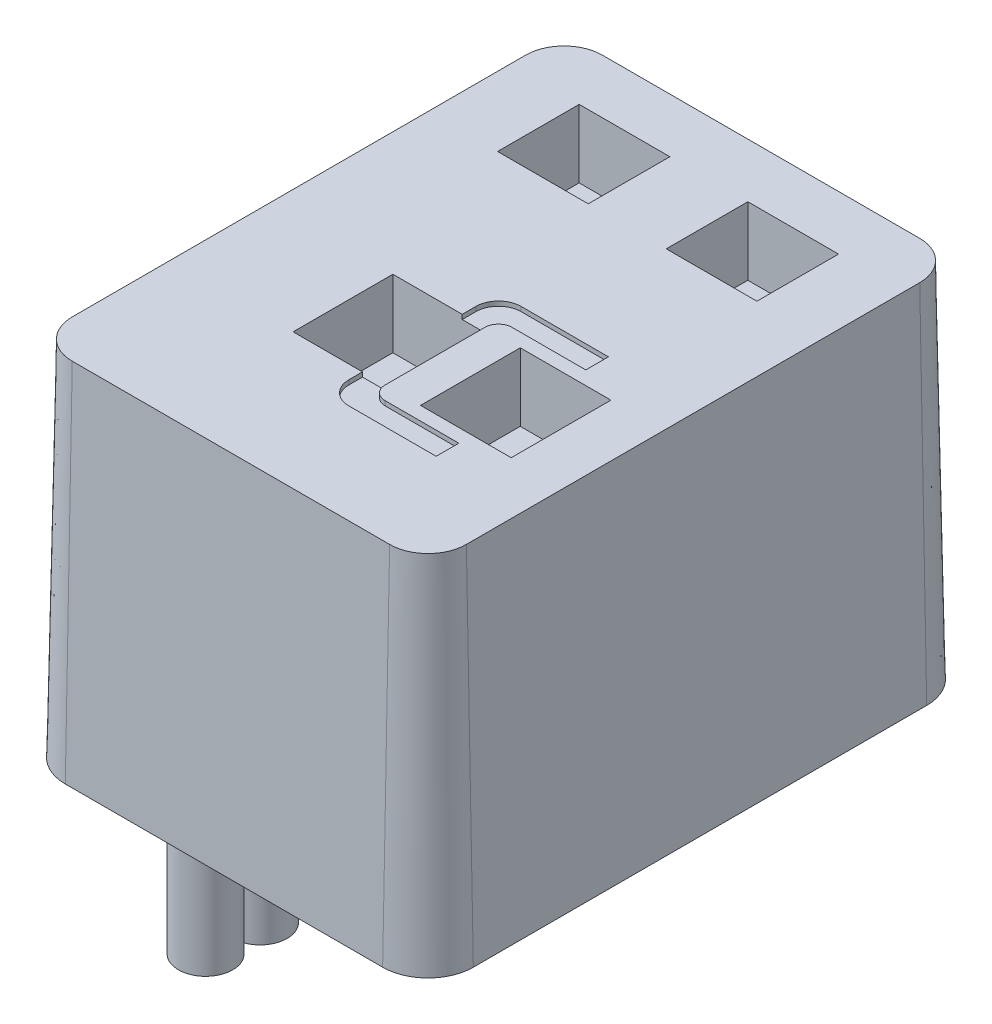
SolidWorks part; units mm, degrees
ref_plane "Alzado" through (0, 0, 0) normal (0, 0, 1) x (1, 0, 0)
ref_plane "Planta" through (0, 0, 0) normal (0, 1, 0) x (1, 0, 0)
ref_plane "Vista lateral" through (0, 0, 0) normal (1, 0, 0) x (0, 0, -1)
ref_plane "Plano1"
sketch "Croquis1" plane through (0, 0, 0) normal (0, 1, 0) x (-1, 0, 0)
  line L0 (4.5, -5) -> (4.5, 5)
  line L1 (3.5, 6) -> (-3.5, 6)
  line L2 (-4.5, 5) -> (-4.5, -5)
  line L3 (-3.5, -6) -> (3.5, -6)
  arc A0 (3.5, -6) -> (4.5, -5) centre (3.5, -5) ccw
  arc A1 (4.5, 5) -> (3.5, 6) centre (3.5, 5) ccw
  arc A2 (-3.5, 6) -> (-4.5, 5) centre (-3.5, 5) ccw
  arc A3 (-4.5, -5) -> (-3.5, -6) centre (-3.5, -5) ccw
  dimension "D1" = 1
  dimension "D2" = 1
extrude "Extrusión1" add sketch "Croquis1" along normal blind 8 draft 1.099
sketch "Croquis2" plane through (0, 8, 0) normal (0, 1, 0) x (-1, 0, 0)
  line L0 (-0.375, 2.85) -> (-0.375, 0.65)
  line L1 (-0.375, 0.65) -> (1.625, 0.65)
  line L2 (1.625, 0.65) -> (1.625, 2.85)
  line L3 (1.625, 2.85) -> (-0.375, 2.85)
  line L4 (-3.185, 2.85) -> (-3.185, 0.65)
  line L5 (-3.185, 0.65) -> (-1.185, 0.65)
  line L6 (-1.185, 0.65) -> (-1.185, 2.85)
  line L7 (-1.185, 2.85) -> (-3.185, 2.85)
  line L8 (-2.905, -2.85) -> (-2.905, -4.65)
  line L9 (-2.905, -4.65) -> (-0.905, -4.65)
  line L10 (-0.905, -4.65) -> (-0.905, -2.85)
  line L11 (-0.905, -2.85) -> (-2.905, -2.85)
  line L12 (0.815, -2.85) -> (0.815, -4.65)
  line L13 (0.815, -4.65) -> (2.815, -4.65)
  line L14 (2.815, -4.65) -> (2.815, -2.85)
  line L15 (2.815, -2.85) -> (0.815, -2.85)
  line L16 (3.5, 5.8465) -> (-3.5, 5.8465) construction
  line L17 (-3.5, -5.8465) -> (3.5, -5.8465) construction
  dimension "D1" = 2
  dimension "D2" = 1.8
  dimension "D3" = 2
  dimension "D4" = 1.8
  dimension "D5" = 10.4965
  dimension "D6" = 2
  dimension "D7" = 2.2
  dimension "D8" = 2
  dimension "D9" = 2.2
  dimension "D10" = 8.6965
extrude "Extrusión2" cut sketch "Croquis2" against normal blind 1.5
sketch "Croquis3" plane through (0, 8, 0) normal (0, 1, 0) x (-1, 0, 0)
  line L0 (0.095, 0.35) -> (0.095, 3.15)
  line L1 (-0.405, 3.65) -> (-2.33, 3.65)
  line L2 (-2.33, 3.65) -> (-2.33, 3.15)
  line L3 (-2.33, 3.15) -> (-0.705, 3.15)
  line L4 (-0.405, 2.85) -> (-0.405, 0.65)
  line L5 (-0.705, 0.35) -> (-2.33, 0.35)
  line L6 (-2.33, 0.35) -> (-2.33, -0.15)
  line L7 (-2.33, -0.15) -> (-0.405, -0.15)
  line L8 (-0.905, -4.65) -> (-0.905, -2.85) construction
  arc A0 (0.095, 3.15) -> (-0.405, 3.65) centre (-0.405, 3.15) ccw
  arc A1 (-0.405, 2.85) -> (-0.705, 3.15) centre (-0.705, 2.85) ccw
  arc A2 (-0.705, 0.35) -> (-0.405, 0.65) centre (-0.705, 0.65) ccw
  arc A3 (-0.405, -0.15) -> (0.095, 0.35) centre (-0.405, 0.35) ccw
  dimension "D1" = 0.3
  dimension "D2" = 0.5
extrude "Extrusión3" cut sketch "Croquis3" against normal blind 0.1
ref_plane "Plano2"
sketch "Croquis4" plane through (1.185, 8, 1.75) normal (0, 0, 1) x (1, 0, 0)
  line L0 (-0.9099, -1.5) -> (-1.8096, -1.5)
  line L1 (-1.8096, -1.5) -> (-1.81, -1.5011)
  line L2 (-1.7042, -2.2146) -> (-1.7042, -2.2454)
  line L3 (-1.8096, -1.5) -> (-1.8096, -2.5003) construction
  arc A0 (-1.5675, -1.8025) -> (-1.81, -1.5011) centre (-1.8121, -1.7511) ccw
  spline S0 degree 2 poles (-1.5621, -1.7511) (-1.5983, -2.1614) (-1.81, -2.3291) knots 1 1 1 2 2 2 weights 1 1 1
  spline S1 degree 2 poles (-1.7042, -2.2454) (-1.7039, -2.4628) (-1.8096, -2.5003) knots 1 1 1 2 2 2 weights 1 1 1
  spline S2 degree 2 poles (-1.8096, -2.5003) (-1.1848, -2.1152) (-0.9099, -1.5) knots 1 1 1 2 2 2 weights 1 1 1
revolve "Revolución3" [suppressed] cut sketch "Croquis4" angle 360 about L3
ref_plane "Plano3"
sketch "Croquis5" plane through (1.185, 8, 1.75) normal (0, 0, 1) x (1, 0, 0)
  line L0 (1.8981, -1.5) -> (0.9979, -1.5)
  line L1 (0.9979, -1.5) -> (0.998, -1.5011)
  line L2 (1.1038, -2.2147) -> (1.1038, -2.2452)
  line L3 (0.9979, -1.5) -> (0.9979, -2.4999) construction
  arc A0 (1.2409, -1.8031) -> (0.998, -1.5011) centre (0.9963, -1.7511) ccw
  spline S0 degree 2 poles (1.1038, -2.2452) (1.1038, -2.4626) (0.9979, -2.4999) knots 1 1 1 2 2 2 weights 1 1 1
  spline S1 degree 2 poles (0.9979, -2.4999) (1.623, -2.1151) (1.8981, -1.5) knots 1 1 1 2 2 2 weights 1 1 1
  spline S2 degree 2 poles (1.2463, -1.7511) (1.2097, -2.1614) (0.998, -2.3291) knots 1 1 1 2 2 2 weights 1 1 1
revolve "Revolución4" [suppressed] cut sketch "Croquis5" angle 360 about L3
sketch "Croquis6" plane through (0, 0, 0) normal (0, -1, 0) x (1, 0, 0)
  arc A0 (-2.1022, 3.7033) -> (-3.3022, 3.7033) centre (-2.7022, 3.7033) ccw
  arc A1 (-3.3022, 3.7033) -> (-2.1022, 3.7033) centre (-2.7022, 3.7033) ccw
  circle A2 centre (-2.7022, 2.5033) radius 0.6
  arc A3 (-3.3022, 1.3033) -> (-2.1022, 1.3033) centre (-2.7022, 1.3033) ccw
  arc A4 (-2.1022, 1.3033) -> (-3.3022, 1.3033) centre (-2.7022, 1.3033) ccw
  dimension "D1" = 1.2
extrude "Saliente-Extruir2" add sketch "Croquis6" along normal blind 4 separate body contours A3 A4 | A2 | A0 A1
